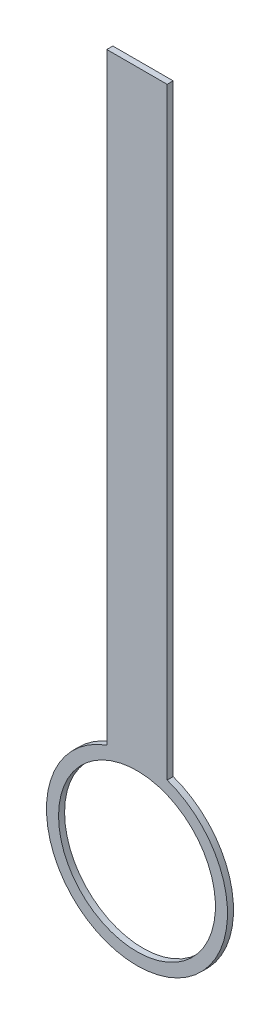
SolidWorks part; units mm, degrees
ref_plane "Front Plane" through (0, 0, 0) normal (0, 0, 1) x (1, 0, 0)
ref_plane "Top Plane" through (0, 0, 0) normal (0, 1, 0) x (1, 0, 0)
ref_plane "Right Plane" through (0, 0, 0) normal (1, 0, 0) x (0, 0, -1)
sketch "Sketch1" plane through (0, 0, 0) normal (0, 0, 1) x (1, 0, 0)
  line L5 (0, 0) -> (20000, 0)
  line L6 (0, 0) -> (0, 200000)
  line L7 (0, 200000) -> (20000, 200000)
  line L8 (20000, 0) -> (20000, 200000)
extrude "Boss-Extrude1" add sketch "Sketch1" along normal blind 2000
sketch "Sketch3" plane through (0, 0, 0) normal (0, 0, -1) x (-1, 0, 0)
  circle A0 centre (-10000, -28000) radius 30000
  circle A2 centre (-10000, -28000) radius 26000
extrude "Boss-Extrude3" add sketch "Sketch3" against normal blind 2000 contours A2 | A0
